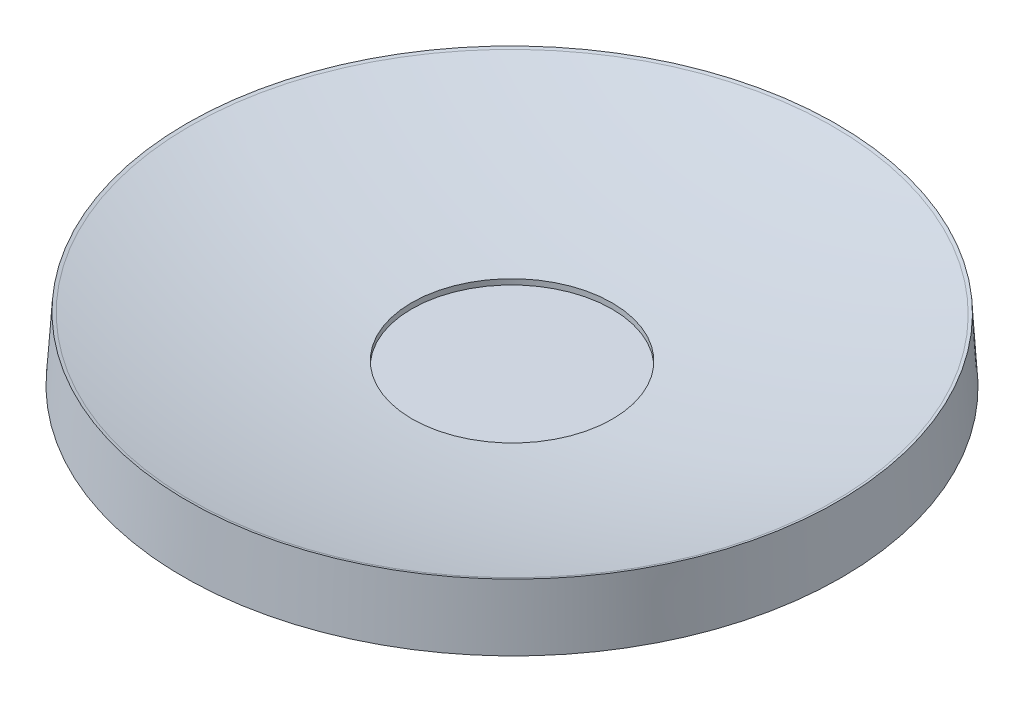
SolidWorks part; units mm, degrees
material "A286 Demir Tabanlı Süperalaşım"
ref_plane "Ön Düzlem" through (0, 0, 0) normal (0, 0, 1) x (1, 0, 0)
ref_plane "Üst Düzlem" through (0, 0, 0) normal (0, 1, 0) x (1, 0, 0)
ref_plane "Sağ Düzlem" through (0, 0, 0) normal (1, 0, 0) x (0, 0, -1)
sketch "Çizim2" plane through (0, 0, 0) normal (0, 0, 1) x (1, 0, 0)
  line L0 (0.0079, 2.4476) -> (0, 0)
  line L1 (4.0188, 2.4475) -> (0.0079, 2.4476)
  line L2 (13.0254, 4.3117) -> (13.1806, 1.7625)
  line L3 (4.0188, 2.4475) -> (4.0188, 2.6655)
  line L4 (12.9052, 4.2779) -> (13.0254, 4.3117)
  line L5 (0.0291, 0) -> (0, 0)
  arc A0 (4.0188, 2.6655) -> (12.9052, 4.2779) centre (0.0291, 49.95) ccw
  arc A1 (0.0291, 0) -> (13.1806, 1.7625) centre (0.0291, 49.95) ccw
revolve "Döndür4" add sketch "Çizim2" angle 360 about L0
